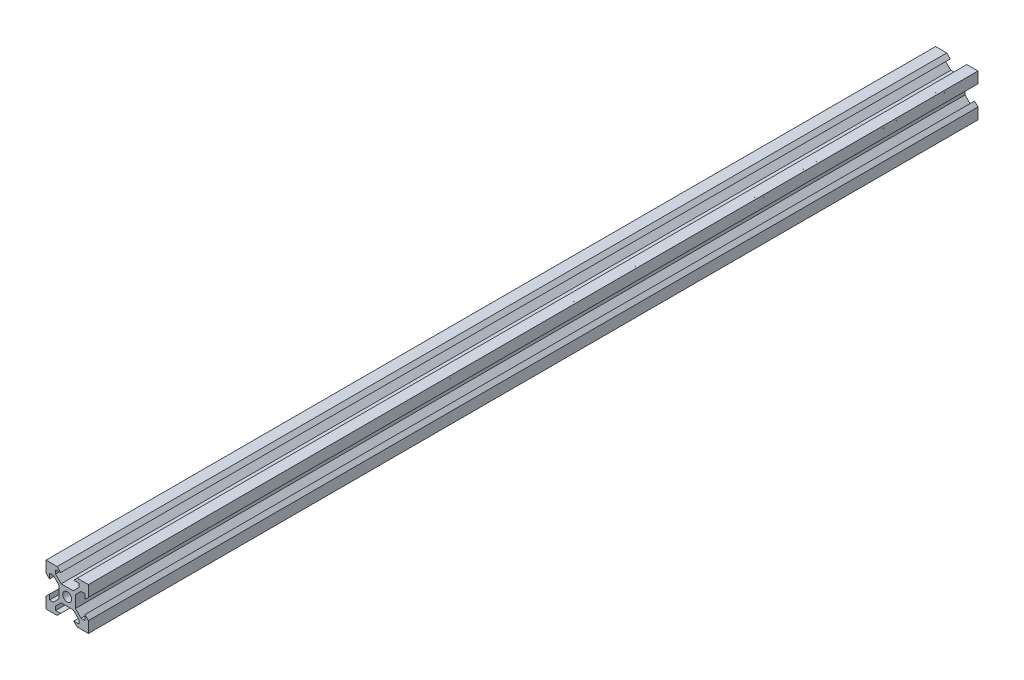
SolidWorks part; units mm, degrees
material "6061-T6 (SS)"
ref_plane "Front Plane" through (0, 0, 0) normal (0, 0, 1) x (1, 0, 0)
ref_plane "Top Plane" through (0, 0, 0) normal (0, 1, 0) x (1, 0, 0)
ref_plane "Right Plane" through (0, 0, 0) normal (1, 0, 0) x (0, 0, -1)
sketch "Sketch1" plane through (0, 0, 0) normal (0, 0, 1) x (1, 0, 0)
  line L0 (2.8343, 3.894) -> (5.5, 6.5588)
  line L1 (2.8343, -3.894) -> (-2.8343, -3.894)
  line L2 (3.8948, -2.8332) -> (3.8948, 2.8332)
  line L3 (2.8343, 3.894) -> (-2.8343, 3.894)
  line L4 (-3.8948, -2.8332) -> (-3.8948, 2.8332)
  line L5 (3.8994, -3.9006) -> (-3.8994, 3.9006) construction
  line L6 (3.9006, 3.8994) -> (-3.9006, -3.8994) construction
  line L7 (10, 4.747) -> (10, 9.9986)
  line L8 (5.5, 6.5588) -> (5.5, 8.3491)
  line L9 (5.5, 8.3491) -> (3.1, 8.3491)
  line L10 (3.1, 8.3491) -> (4.75, 9.9986)
  line L11 (4.75, 9.9986) -> (10, 9.9986)
  line L12 (8.35, 3.0975) -> (10, 4.747)
  line L13 (8.3507, 5.4975) -> (8.35, 3.0975)
  line L14 (6.5605, 5.498) -> (8.3507, 5.4975)
  line L15 (3.8948, 2.8332) -> (6.5605, 5.498)
  line L16 (0, -55) -> (0, 55) construction
  line L17 (-3.8948, 2.8332) -> (-6.5605, 5.498)
  line L18 (-6.5605, 5.498) -> (-8.3507, 5.4975)
  line L19 (-8.3507, 5.4975) -> (-8.35, 3.0975)
  line L20 (-8.35, 3.0975) -> (-10, 4.747)
  line L21 (-4.75, 9.9986) -> (-10, 9.9986)
  line L22 (-3.1, 8.3491) -> (-4.75, 9.9986)
  line L23 (-5.5, 8.3491) -> (-3.1, 8.3491)
  line L24 (-5.5, 6.5588) -> (-5.5, 8.3491)
  line L25 (-10, 4.747) -> (-10, 9.9986)
  line L26 (-2.8343, 3.894) -> (-5.5, 6.5588)
  line L27 (55, 0) -> (-55, 0) construction
  line L28 (3.8948, -2.8332) -> (6.5605, -5.498)
  line L29 (2.8343, -3.894) -> (5.5, -6.5588)
  line L30 (-3.8948, -2.8332) -> (-6.5605, -5.498)
  line L31 (-2.8343, -3.894) -> (-5.5, -6.5588)
  line L32 (-8.3507, -5.4975) -> (-8.35, -3.0975)
  line L33 (-8.35, -3.0975) -> (-10, -4.747)
  line L34 (8.3507, -5.4975) -> (8.35, -3.0975)
  line L35 (8.35, -3.0975) -> (10, -4.747)
  line L36 (-10, -4.747) -> (-10, -9.9986)
  line L37 (-5.5, -6.5588) -> (-5.5, -8.3491)
  line L38 (-5.5, -8.3491) -> (-3.1, -8.3491)
  line L39 (-3.1, -8.3491) -> (-4.75, -9.9986)
  line L40 (-4.75, -9.9986) -> (-10, -9.9986)
  line L41 (-6.5605, -5.498) -> (-8.3507, -5.4975)
  line L42 (6.5605, -5.498) -> (8.3507, -5.4975)
  line L43 (4.75, -9.9986) -> (10, -9.9986)
  line L44 (3.1, -8.3491) -> (4.75, -9.9986)
  line L45 (5.5, -8.3491) -> (3.1, -8.3491)
  line L46 (5.5, -6.5588) -> (5.5, -8.3491)
  line L47 (10, -4.747) -> (10, -9.9986)
  circle A0 centre (0, 0) radius 2.1
  point P0 (0, 0)
  dimension "D6" = 4.2
  dimension "D1" = 7.8
  dimension "D2" = 20
  dimension "D3" = 11
  dimension "D4" = 9.5
  dimension "D5" = 6.2
  dimension "D7" = 1.5
extrude "Boss-Extrude1" add sketch "Sketch1" along normal blind 420
